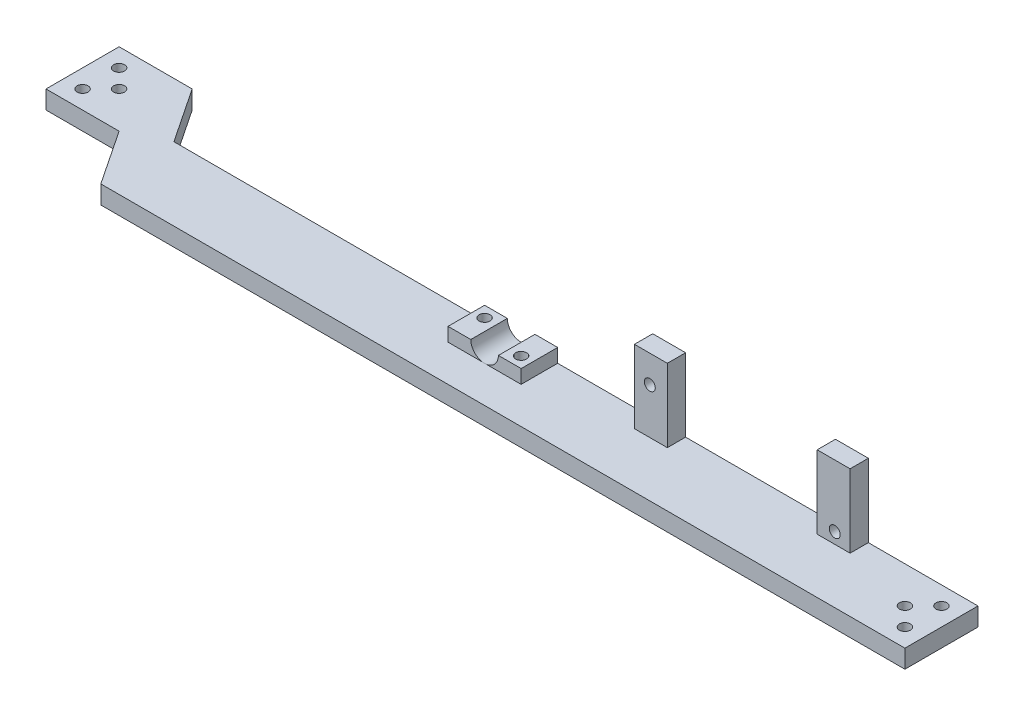
SolidWorks part; units mm, degrees
ref_plane "Front Plane" through (0, 0, 0) normal (0, 0, 1) x (1, 0, 0)
ref_plane "Top Plane" through (0, 0, 0) normal (0, 1, 0) x (1, 0, 0)
ref_plane "Right Plane" through (0, 0, 0) normal (1, 0, 0) x (0, 0, -1)
sketch "Sketch1" plane through (0, 0, 0) normal (0, 1, 0) x (1, 0, 0)
  line L0 (-26.3058, -6.6206) -> (193.6942, -6.6206)
  line L1 (-56.3058, 28.3794) -> (-36.3058, 28.3794)
  line L2 (-56.3058, 28.3794) -> (-56.3058, 8.3794)
  line L3 (-56.3058, 8.3794) -> (-36.3058, 8.3794)
  line L4 (193.6942, 13.3794) -> (193.6942, -6.6206)
  line L5 (-26.3058, 13.3794) -> (193.6942, 13.3794)
  line L6 (-36.3058, 8.3794) -> (-26.3058, -6.6206)
  line L7 (-36.3058, 28.3794) -> (-26.3058, 13.3794)
  dimension "D1" = 10
  dimension "D2" = 20
  dimension "D3" = 220
  dimension "D4" = 220
  dimension "D5" = 20
  dimension "D6" = 20
  dimension "D7" = 15
extrude "Boss-Extrude1" add sketch "Sketch1" along normal blind 5
sketch "Sketch2" plane through (0, 5, 0) normal (0, 1, 0) x (1, 0, 0)
  line L1 (58.6942, 13.3794) -> (78.6942, 13.3794)
  line L2 (58.6942, 13.3794) -> (58.6942, 3.3794)
  line L3 (58.6942, 3.3794) -> (78.6942, 3.3794)
  line L4 (78.6942, 13.3794) -> (78.6942, 3.3794)
  line L5 (193.6942, -6.6206) -> (193.6942, 13.3794) construction
  line L9 (193.6942, 13.3794) -> (-26.3058, 13.3794) construction
  dimension "D1" = 20
  dimension "D2" = 10
  dimension "D3" = 115
  dimension "D4" = 0
extrude "Boss-Extrude2" add sketch "Sketch2" along normal blind 3.75
sketch "Sketch3" plane through (0, 0, -3.3794) normal (0, 0, 1) x (1, 0, 0)
  line L0 (58.6942, 8.75) -> (78.6942, 8.75) construction
  line L1 (78.6942, 8.75) -> (78.6942, 5) construction
  circle A0 centre (68.6942, 8.75) radius 3.775
  dimension "D1" = 7.55
  dimension "D2" = 10
extrude "Cut-Extrude1" cut sketch "Sketch3" against normal blind 10
sketch "Sketch4" plane through (0, 8.75, 0) normal (0, 1, 0) x (1, 0, 0)
  line L0 (64.9192, 13.3794) -> (58.6942, 13.3794) construction
  line L1 (58.6942, 13.3794) -> (58.6942, 3.3794) construction
  line L3 (78.6942, 3.3794) -> (78.6942, 13.3794) construction
  line L4 (72.4692, 3.3794) -> (78.6942, 3.3794) construction
  circle A0 centre (75.6942, 6.3794) radius 1.5
  circle A2 centre (61.6942, 10.3794) radius 1.5
  dimension "D1" = 3
  dimension "D2" = 3
  dimension "D3" = 3
  dimension "D4" = 3
  dimension "D5" = 3
  dimension "D6" = 3
sketch "Sketch7" plane through (0, 5, 0) normal (0, 1, 0) x (1, 0, 0)
  line L0 (193.6942, -6.6206) -> (193.6942, 13.3794) construction
  line L1 (193.6942, 13.3794) -> (78.6942, 13.3794) construction
  line L2 (-26.3058, -6.6206) -> (193.6942, -6.6206) construction
  line L3 (-36.3058, 28.3794) -> (-56.3058, 28.3794) construction
  line L4 (-56.3058, 28.3794) -> (-56.3058, 8.3794) construction
  line L5 (-56.3058, 8.3794) -> (-36.3058, 8.3794) construction
  circle A0 centre (-51.3058, 23.3794) radius 1.5
  circle A1 centre (-51.3058, 13.3794) radius 1.5
  circle A2 centre (188.6942, -1.6206) radius 1.5
  circle A3 centre (188.6942, 8.3794) radius 1.5
  circle A4 centre (183.6942, 3.3794) radius 1.5
  circle A5 centre (-46.3058, 18.3794) radius 1.5
  dimension "D1" = 3
  dimension "D2" = 3
  dimension "D3" = 5
  dimension "D4" = 5
  dimension "D5" = 5
  dimension "D6" = 5
  dimension "D7" = 3
  dimension "D8" = 3
  dimension "D9" = 5
  dimension "D10" = 5
  dimension "D11" = 5
  dimension "D12" = 5
  dimension "D13" = 3
  dimension "D14" = 10
  dimension "D15" = 10
  dimension "D16" = 3
  dimension "D17" = 10
  dimension "D18" = 10
extrude "Cut-Extrude3" cut sketch "Sketch7" against normal blind 5
extrude "Cut-Extrude2" cut sketch "Sketch4" against normal blind 4
sketch "Sketch8" plane through (0, 5, 0) normal (0, 1, 0) x (1, 0, 0)
  line L0 (193.6942, 13.3794) -> (78.6942, 13.3794) construction
  line L1 (104.6942, 8.3794) -> (113.6942, 8.3794)
  line L2 (104.6942, 8.3794) -> (104.6942, 13.3794)
  line L3 (104.6942, 13.3794) -> (113.6942, 13.3794)
  line L4 (113.6942, 8.3794) -> (113.6942, 13.3794)
  line L5 (193.6942, -6.6206) -> (193.6942, 13.3794) construction
  line L6 (154.6942, 8.3794) -> (163.6942, 8.3794)
  line L7 (154.6942, 8.3794) -> (154.6942, 13.3794)
  line L8 (154.6942, 13.3794) -> (163.6942, 13.3794)
  line L9 (163.6942, 8.3794) -> (163.6942, 13.3794)
  dimension "D1" = 41
  dimension "D2" = 9
  dimension "D3" = 9
  dimension "D4" = 5
  dimension "D5" = 5
  dimension "D6" = 30
extrude "Boss-Extrude3" add sketch "Sketch8" along normal blind 20
sketch "Sketch9" plane through (0, 0, -8.3794) normal (0, 0, 1) x (1, 0, 0)
  line L0 (154.6942, 5) -> (163.6942, 5) construction
  line L1 (154.6942, 25) -> (154.6942, 5) construction
  line L2 (113.6942, 25) -> (113.6942, 5) construction
  circle A0 centre (108.8942, 17.5) radius 1.5
  circle A1 centre (159.4942, 8) radius 1.5
  dimension "D1" = 3
  dimension "D2" = 3
  dimension "D3" = 3
  dimension "D4" = 9.5
  dimension "D5" = 4.8
  dimension "D6" = 4.8
extrude "Cut-Extrude4" cut sketch "Sketch9" against normal blind 5
